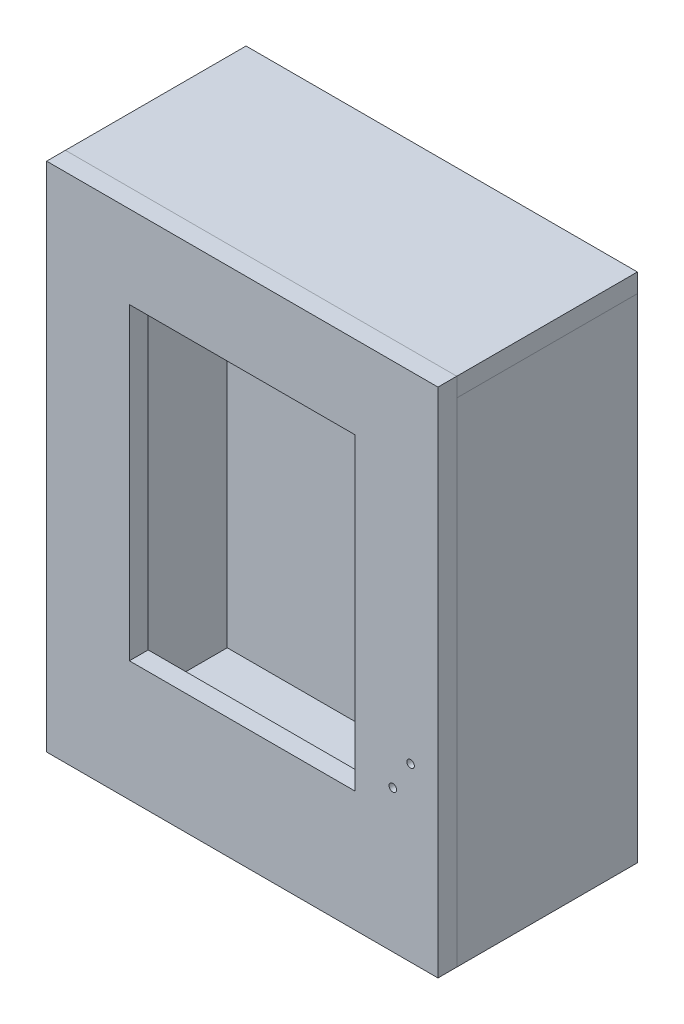
SolidWorks part; units mm, degrees
ref_plane "Default Plane" through (139.7, 34.925, -144.4625) normal (0, 0, -1) x (-1, 0, 0)
sketch3d "Bounding-Box_Cut-List-Item1"
  line L0 (279.4, -15.875, 0) -> (0, -15.875, 0) construction
  line L1 (0, -15.875, 0) -> (0, 60.325, 0) construction
  line L2 (0, 60.325, 0) -> (279.4, 60.325, 0) construction
  line L3 (279.4, 60.325, 0) -> (279.4, -15.875, 0) construction
  line L4 (279.4, -15.875, 15.875) -> (0, -15.875, 15.875) construction
  line L5 (0, -15.875, 15.875) -> (0, 60.325, 15.875) construction
  line L6 (0, 60.325, 15.875) -> (279.4, 60.325, 15.875) construction
  line L7 (279.4, 60.325, 15.875) -> (279.4, -15.875, 15.875) construction
  line L8 (279.4, -15.875, 0) -> (279.4, -15.875, 15.875) construction
  line L9 (0, -15.875, 0) -> (0, -15.875, 15.875) construction
  line L10 (0, 60.325, 0) -> (0, 60.325, 15.875) construction
  line L11 (279.4, 60.325, 0) -> (279.4, 60.325, 15.875) construction
other "Markup2"
sketch "Sketch17" plane through (-171.45, -231.775, 7.9375) normal (0, 0, 1) x (1, 0, 0)
ref_plane "Front Plane" through (0, 0, 0) normal (0, 0, 1) x (1, 0, 0)
ref_plane "Top Plane" through (0, 0, 0) normal (0, 1, 0) x (1, 0, 0)
ref_plane "Right Plane" through (0, 0, 0) normal (1, 0, 0) x (0, 0, -1)
sketch "Sketch1" plane through (0, 0, 0) normal (0, 0, 1) x (1, 0, 0)
  line L0 (-165.1, 200.025) -> (165.1, 200.025)
  line L1 (-95.25, -130.175) -> (95.25, -130.175)
  line L2 (-95.25, -130.175) -> (-95.25, 130.175)
  line L3 (-95.25, 130.175) -> (95.25, 130.175)
  line L4 (95.25, -130.175) -> (95.25, 130.175)
  line L5 (-95.25, -130.175) -> (95.25, 130.175) construction
  line L6 (-95.25, 130.175) -> (95.25, -130.175) construction
  line L7 (165.1, -231.775) -> (165.1, 200.025)
  line L8 (-165.1, -231.775) -> (165.1, -231.775)
  line L9 (-165.1, -231.775) -> (-165.1, 200.025)
  circle A0 centre (127, -111.775) radius 3.175
  circle A1 centre (142, -86.775) radius 3.175
  point P0 (0, 0)
  point P14 (0, 0)
  point P15 (127, -109.814)
  dimension "D5" = 6.35
  dimension "D8" = 6.35
  dimension "D12" = 120
  dimension "D1" = 190.5
  dimension "D2" = 260.35
  dimension "D4" = 38.1
  dimension "D6" = 25
  dimension "D7" = 15
  dimension "D3" = 69.85
  dimension "D9" = 101.6
  dimension "D10" = 69.85
  dimension "D11" = 69.85
extrude "Boss-Extrude1" add sketch "Sketch1" along normal mid plane 15.875
sketch "Sketch3" plane through (165.1, 0, 0) normal (1, 0, 0) x (0, 0, -1)
  line L0 (-7.9375, -231.775) -> (7.9375, -231.775) construction
  line L1 (7.9375, 184.15) -> (160.3375, 184.15)
  line L2 (7.9375, 184.15) -> (7.9375, -231.775)
  line L3 (7.9375, -231.775) -> (160.3375, -231.775)
  line L4 (160.3375, 184.15) -> (160.3375, -231.775)
  line L5 (7.9375, 184.15) -> (160.3375, -231.775) construction
  line L6 (7.9375, -231.775) -> (160.3375, 184.15) construction
  line L7 (7.9375, -231.775) -> (7.9375, 200.025) construction
  line L8 (-7.9375, -231.775) -> (-7.9375, 200.025) construction
  line L10 (-7.9375, 200.025) -> (7.9375, 200.025) construction
  point P4 (84.1375, -23.8125)
  dimension "D1" = 168.275
  dimension "D2" = 152.4
  dimension "D3" = 15.875
extrude "Boss-Extrude2" add sketch "Sketch3" against normal blind 15.875 separate body
mirror "Mirror1" about plane through (0, 0, 0) normal (1, 0, 0) of bodies 102
sketch "Sketch8" plane through (0, 0, -160.3375) normal (0, 0, -1) x (-1, 0, 0)
  line L0 (-149.225, -231.775) -> (-149.225, 184.15) construction
  line L1 (-149.225, 184.15) -> (149.225, 184.15)
  line L2 (-149.225, 184.15) -> (-149.225, -231.775)
  line L3 (-149.225, -231.775) -> (149.225, -231.775)
  line L4 (149.225, 184.15) -> (149.225, -231.775)
  line L5 (-149.225, 184.15) -> (149.225, -231.775) construction
  line L6 (-149.225, -231.775) -> (149.225, 184.15) construction
  line L7 (-165.1, 200.025) -> (165.1, 200.025) construction
  circle A0 centre (-130.175, -200.025) radius 9.6012
  point P4 (0, -23.8125)
  dimension "D2" = 19.2024
  dimension "D1" = 15.875
  dimension "D3" = 31.75
  dimension "D4" = 19.05
extrude "Boss-Extrude6" add sketch "Sketch8" against normal blind 15.875 from offset 15.875 separate body offset against normal yes
sketch "Sketch11" plane through (0, -231.775, 0) normal (0, -1, 0) x (1, 0, 0)
  line L0 (-149.225, -7.9375) -> (-149.225, -160.3375) construction
  line L1 (-149.225, -7.9375) -> (149.225, -7.9375)
  line L2 (-149.225, -7.9375) -> (-149.225, -128.5875)
  line L3 (-149.225, -128.5875) -> (149.225, -128.5875)
  line L4 (149.225, -7.9375) -> (149.225, -128.5875)
  line L5 (-149.225, -7.9375) -> (149.225, -128.5875) construction
  line L6 (-149.225, -128.5875) -> (149.225, -7.9375) construction
  line L7 (-165.1, -7.9375) -> (165.1, -7.9375) construction
  point P4 (0, -68.2625)
extrude "Boss-Extrude7" add sketch "Sketch11" against normal blind 15.875 separate body
sketch "Sketch14" plane through (0, 200.025, 0) normal (0, 1, 0) x (1, 0, 0)
  line L0 (149.225, 7.9375) -> (-149.225, 7.9375) construction
  line L1 (-165.1, 160.3375) -> (165.1, 160.3375)
  line L2 (-165.1, 160.3375) -> (-165.1, 7.9375)
  line L3 (-165.1, 7.9375) -> (165.1, 7.9375)
  line L4 (165.1, 160.3375) -> (165.1, 7.9375)
  line L5 (-165.1, 160.3375) -> (165.1, 7.9375) construction
  line L6 (-165.1, 7.9375) -> (165.1, 160.3375) construction
  line L7 (165.1, 160.3375) -> (165.1, 7.9375) construction
  point P4 (0, 84.1375)
extrude "Boss-Extrude8" add sketch "Sketch14" against normal blind 15.875 separate body
sketch "Sketch7" plane through (0, 0, 0) normal (1, 0, 0) x (0, 0, -1)
  line L0 (144.4625, 95.25) -> (144.4625, 34.925)
  line L2 (144.4625, 34.925) -> (160.3375, 19.05)
  line L3 (160.3375, 19.05) -> (160.3375, 95.25)
  line L4 (160.3375, 95.25) -> (144.4625, 95.25)
  line L11 (160.3375, 184.15) -> (7.9375, 184.15) construction
  line L13 (144.4625, -209.6262) -> (144.4625, -190.4238) construction
  dimension "D1" = 76.2
  dimension "D2" = 15.875
  dimension "D3" = 45
  dimension "D4" = 88.9
extrude "Boss-Extrude5" add sketch "Sketch7" along normal mid plane 279.4 separate body
